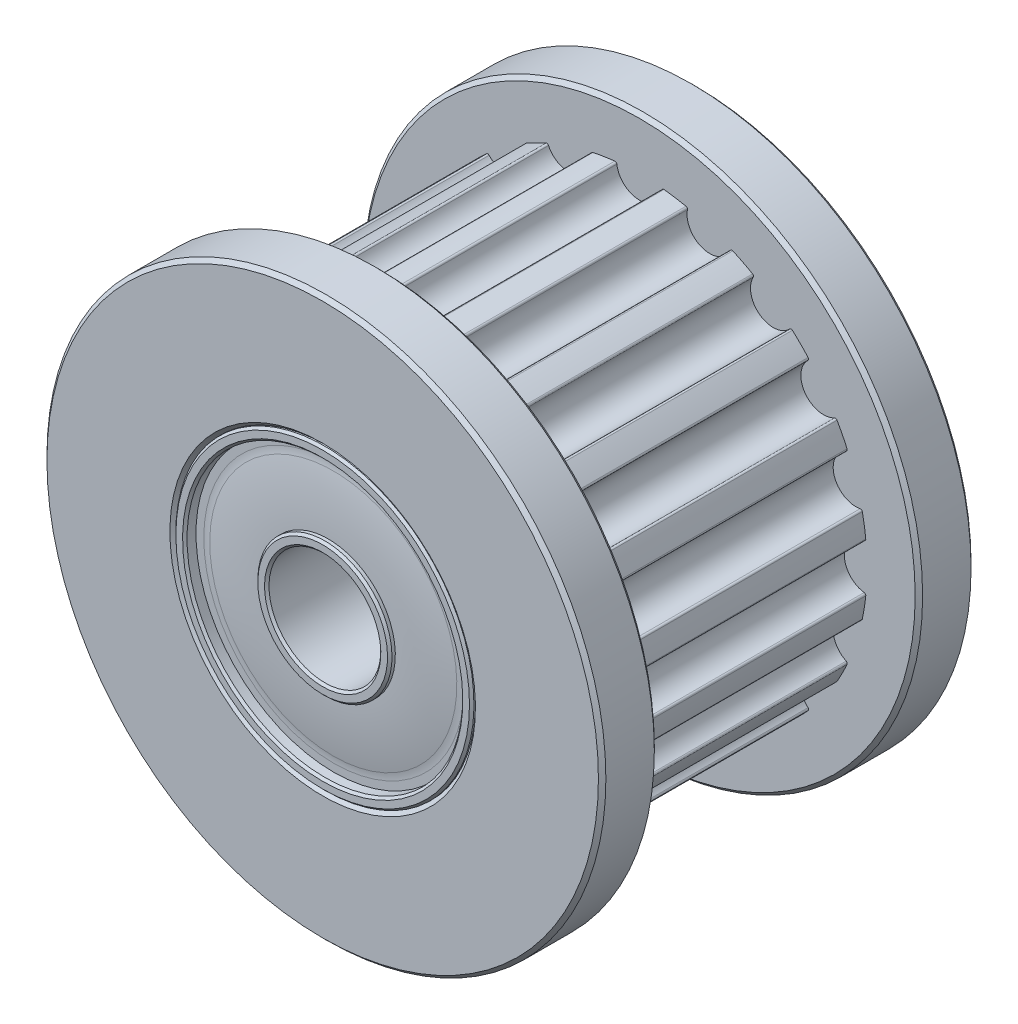
SolidWorks part; units mm, degrees
ref_plane "Front" through (0, 0, 0) normal (0, 0, 1) x (1, 0, 0)
ref_plane "Top" through (0, 0, 0) normal (0, 1, 0) x (1, 0, 0)
ref_plane "Right" through (0, 0, 0) normal (1, 0, 0) x (0, 0, -1)
sketch "Sketch1" plane through (0, 0, 0) normal (1, 0, 0) x (0, 0, -1)
  line L0 (-5, 0) -> (5, 0) construction
  line L1 (5, 7.5) -> (5, -7.5) construction
  line L2 (5, 7.5) -> (3.5, 7.5) construction
  line L3 (5, 1.5) -> (5, -1.5) construction
  line L4 (5, 6.11) -> (5, -6.11) construction
  line L5 (3, 0) -> (-3, 0) construction
  line L6 (3.5, 7.5) -> (3.5, 6.11) construction
  line L7 (5, 4) -> (2, 4) construction
  line L8 (2, 4) -> (2, 1.5) construction
  line L9 (2, 1.5) -> (5, 1.5) construction
  line L10 (5, 4) -> (5, -4) construction
  line L11 (-5, 0) -> (-5, 7.5) construction
  line L12 (-5, 7.5) -> (-3.5, 7.5) construction
  line L13 (-3.5, 7.5) -> (-3.5, 6.11) construction
  line L14 (-3.5, 6.11) -> (3.5, 6.11) construction
  line L15 (3.5, 6.11) -> (3.5, -6.11) construction
  line L16 (3.5, -6.11) -> (-3.5, -6.11) construction
  line L17 (-3.5, -6.11) -> (-3.5, 6.11) construction
  line L18 (0, -2.5) -> (0, 2.5) construction
  point P15 (5, 0)
  point P22 (3.5, 0)
  point P24 (-3, -6.11)
  point P25 (3, -6.11)
  point P29 (0, 0)
  dimension "Width" = 10
  dimension "OD" = 15
  dimension "ID" = 3
  dimension "Diameter" = 12.22
  dimension "Groove Depth" = 1.39
  dimension "For Maximum Belt Width" = 6
  dimension "For Shaft Diameter" = 3
  dimension "Bearing Diameter" = 8
  dimension "Bearing Width" = 3
  dimension "Inside Width" = 7
  dimension "Wall Thickness" = 1.5
  dimension "D1" = 5
sketch "Sketch5" plane through (0, 0, 0) normal (0, 0, 1) x (1, 0, 0)
  circle A0 centre (0, 0) radius 7.5 construction
  circle A1 centre (0, 0) radius 6.11 construction
  circle A2 centre (0, 0) radius 1.5 construction
  point P5 (0, 0)
  point P9 (-6.11, 0)
  point P10 (-7.5, 0)
  point P13 (0, 6.11)
sketch "Sketch2" plane through (0, 0, 0) normal (1, 0, 0) x (0, 0, -1)
  line L0 (5, 1.5) -> (2, 1.5)
  line L1 (5, 1.5) -> (5, 1.8)
  line L2 (5, 7.5) -> (5, -7.5) construction
  line L3 (5, 1.8) -> (4.7, 1.8) construction
  line L4 (4.85, 3.7) -> (4.85, 1.8) construction
  line L5 (5, 4) -> (2, 4)
  line L6 (4.7, 3.4) -> (4.7, 3.7)
  line L7 (5, 4) -> (5, 3.7)
  line L8 (5, 3.7) -> (4.7, 3.7)
  line L9 (4.7, 3.7) -> (4.7, 1.8) construction
  line L10 (2, 4) -> (2, 1.5)
  line L11 (4.85, 1.8) -> (5, 1.8)
  arc A0 (4.7, 3.4) -> (4.85, 1.8) centre (-3.7583, 1.8) cw
  dimension "D1" = 0.3
revolve "Revolve1" add sketch "Sketch2" angle 360 about L0
chamfer "Chamfer2" distance 0.06 angle 45 4 edges at (0, -1.8, -5) (0, -1.5, -5) (0, -3.7, -5) (0, -4, -5)
fillet "Fillet2" radius 1 1 edges at (0, -3.4, -4.7)
mirror "Mirror1" about plane through (0, 0, 0) normal (0, 0, 1) of bodies 108
sketch "Sketch3" plane through (0, 0, 0) normal (1, 0, 0) x (0, 0, -1)
  line L0 (3.5, 7.5) -> (5, 7.5)
  line L1 (5, 7.5) -> (5, 4)
  line L2 (5, 7.5) -> (5, -7.5) construction
  line L3 (-5, 4) -> (-2, 4)
  line L4 (-2, 4) -> (-2, 2.5)
  line L5 (-2, 2.5) -> (2, 2.5)
  line L6 (2, 2.5) -> (2, 4)
  line L8 (2, 4) -> (5, 4)
  line L9 (3.5, 7.5) -> (3.5, 6.11)
  line L10 (3.5, 6.11) -> (-3.5, 6.11)
  line L11 (0, 6.11) -> (0, 4) construction
  line L12 (-5, 4) -> (5, 4) construction
  line L13 (-3.5, 7.5) -> (-3.5, 6.11)
  line L19 (-5, 7.5) -> (-5, 4)
  line L20 (-3.5, 7.5) -> (-5, 7.5)
revolve "Revolve2" add sketch "Sketch3" angle 360 about L0
chamfer "Chamfer1" distance 0.1 angle 45 6 edges at (0, -7.5, -5) (0, -7.5, -3.5) (0, -7.5, 3.5) (0, -7.5, 5) (0, -4, -5) (0, -4, 5)
sketch "Sketch4" plane through (0, 0, 0) normal (0, 0, 1) x (1, 0, 0)
  line L0 (-0.611, 6.11) -> (0.611, 6.11)
  line L1 (-0.611, 6.11) -> (-0.611, 5.554) construction
  line L2 (-0.611, 5.554) -> (0.611, 5.554) construction
  line L3 (0.611, 5.554) -> (0.611, 6.11) construction
  line L4 (0, 6.11) -> (0, 5.554) construction
  arc A0 (0.611, 6.11) -> (-0.611, 6.11) centre (0, 6.11) cw
  dimension "D1" = 0.556
  dimension "D3" = 1.222
extrude "Cut-Extrude1" cut sketch "Sketch4" against normal up to surface and the other way up to surface
fillet "Fillet1" radius 0.05 2 edges at (-0.6102, 6.0795, 0) (0.6102, 6.0795, 0)
pattern_circular "CirPattern3" count 20 over 360 about axis through (0, 0, 0) along (0, 0, 1) of "Cut-Extrude1", "Fillet1"
equation "\"D1@Sketch4\"=\"Groove Depth@Sketch1\"/2.5"
equation "\"D3@Sketch4\"=\"Diameter@Sketch1\"/10"
equation "\"D1@Sketch1\"=\"ID@Sketch1\"+2"
